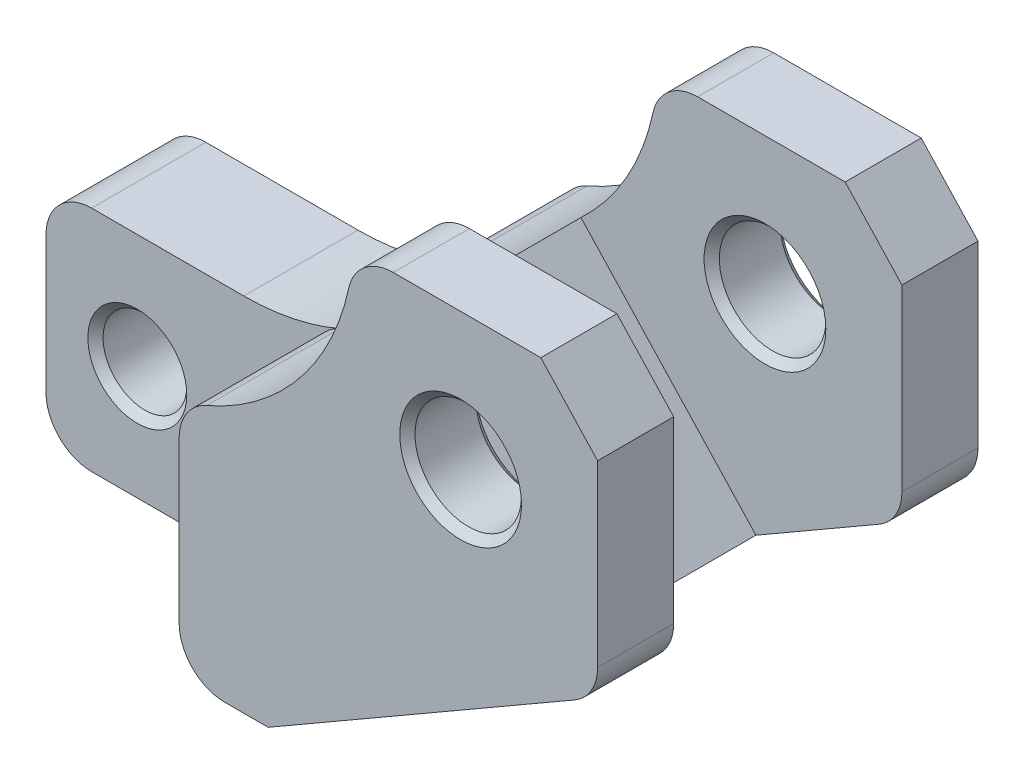
SolidWorks part; units mm, degrees
ref_plane "Front Plane" through (0, 0, 0) normal (0, 0, 1) x (1, 0, 0)
ref_plane "Top Plane" through (0, 0, 0) normal (0, 1, 0) x (1, 0, 0)
ref_plane "Right Plane" through (0, 0, 0) normal (1, 0, 0) x (0, 0, -1)
sketch "Sketch1" plane through (0, 0, 0) normal (0, 0, 1) x (1, 0, 0)
  line L0 (0, 24000) -> (0, 6000)
  line L1 (6000, 0) -> (46698.7298, 0)
  line L2 (46698.7298, 0) -> (87000, 23267.9492)
  line L3 (90000, 28464.1016) -> (90000, 60000)
  line L4 (90000, 60000) -> (63148.3512, 60000)
  line L5 (6000, 30000) -> (26000, 30000)
  arc A0 (26000, 30000) -> (57282.8221, 55263.1579) centre (26000, 62000) ccw
  arc A1 (87000, 23267.9492) -> (90000, 28464.1016) centre (84000, 28464.1016) ccw
  arc A2 (63148.3512, 60000) -> (57282.8221, 55263.1579) centre (63148.3512, 54000) ccw
  arc A3 (0, 6000) -> (6000, 0) centre (6000, 6000) ccw
  arc A4 (0, 24000) -> (6000, 30000) centre (6000, 24000) cw
  point P9 (28220.4792, 51998.0458)
  point P10 (90000, 41829.3302)
  point P11 (90000, 0)
  point P12 (90000, 32721.6643)
  point P15 (90000, 25000)
  point P20 (0, 0)
  point P23 (0, 0)
  dimension "D1" = 32000
  dimension "D8" = 6000
  dimension "D2" = 90000
  dimension "D3" = 30
  dimension "D4" = 25000
  dimension "D5" = 60000
  dimension "D6" = 30000
  dimension "D7" = 26000
extrude "Boss-Extrude1" add sketch "Sketch1" along normal mid plane 50000
chamfer "Chamfer1" distance 8000 angle 43 1 edges at (90000, 60000, 0)
sketch "Sketch4" plane through (0, 0, 0) normal (0, 0, 1) x (1, 0, 0)
  line L0 (70814.2066, 13923.077) -> (47814.1845, 38587.5812)
  line L10 (90000, 28464.1016) -> (90000, 52000)
  line L11 (90000, 52000) -> (82539.8793, 60000)
  line L12 (82539.8793, 60000) -> (63148.3512, 60000)
  line L13 (26000, 30000) -> (6000, 30000)
  line L14 (0, 24000) -> (0, 6000)
  line L15 (6000, 0) -> (46698.7298, 0)
  line L16 (46698.7298, 0) -> (87000, 23267.9492)
  line L17 (90000, 28464.1016) -> (90000, 52000)
  line L18 (90000, 52000) -> (82539.8793, 60000)
  line L19 (82539.8793, 60000) -> (63148.3512, 60000)
  line L23 (70814.2066, 13923.077) -> (87000, 23267.9492)
  arc A6 (63148.3512, 60000) -> (57282.8221, 55263.1579) centre (63148.3512, 54000) ccw
  arc A7 (26000, 30000) -> (57282.8221, 55263.1579) centre (26000, 62000) ccw
  arc A8 (6000, 30000) -> (0, 24000) centre (6000, 24000) ccw
  arc A9 (0, 6000) -> (6000, 0) centre (6000, 6000) ccw
  arc A10 (87000, 23267.9492) -> (90000, 28464.1016) centre (84000, 28464.1016) ccw
  arc A11 (63148.3512, 60000) -> (57282.8221, 55263.1579) centre (63148.3512, 54000) ccw
  arc A12 (47814.1845, 38587.5812) -> (57282.8221, 55263.1579) centre (26000, 62000) ccw
  arc A15 (87000, 23267.9492) -> (90000, 28464.1016) centre (84000, 28464.1016) ccw
  dimension "D1" = 40000
  dimension "D2" = 0
extrude "Cut-Extrude1" cut sketch "Sketch4" against normal mid plane 30000
sketch "Sketch5" plane through (0, 0, 25000) normal (0, 0, 1) x (1, 0, 0)
  line L0 (35000, 0) -> (35000, 31291.6949)
  line L1 (6000, 0) -> (46698.7298, 0) construction
  line L9 (90000, 28464.1016) -> (90000, 52000)
  line L10 (90000, 52000) -> (82539.8793, 60000)
  line L11 (82539.8793, 60000) -> (63148.3512, 60000)
  line L12 (26000, 30000) -> (6000, 30000)
  line L13 (0, 24000) -> (0, 6000)
  line L14 (6000, 0) -> (46698.7298, 0)
  line L15 (46698.7298, 0) -> (87000, 23267.9492)
  line L19 (26000, 30000) -> (6000, 30000)
  line L20 (0, 24000) -> (0, 6000)
  line L21 (6000, 0) -> (35000, 0)
  arc A0 (26000, 30000) -> (57282.8221, 55263.1579) centre (26000, 62000) ccw construction
  arc A6 (63148.3512, 60000) -> (57282.8221, 55263.1579) centre (63148.3512, 54000) ccw
  arc A7 (26000, 30000) -> (57282.8221, 55263.1579) centre (26000, 62000) ccw
  arc A8 (6000, 30000) -> (0, 24000) centre (6000, 24000) ccw
  arc A9 (0, 6000) -> (6000, 0) centre (6000, 6000) ccw
  arc A10 (87000, 23267.9492) -> (90000, 28464.1016) centre (84000, 28464.1016) ccw
  arc A12 (26000, 30000) -> (35000, 31291.6949) centre (26000, 62000) ccw
  arc A13 (6000, 30000) -> (0, 24000) centre (6000, 24000) ccw
  arc A14 (0, 6000) -> (6000, 0) centre (6000, 6000) ccw
  dimension "D2" = 35000
  dimension "D1" = 0
extrude "Cut-Extrude2" cut sketch "Sketch5" against normal blind 17500
mirror "Mirror2" about plane through (0, 0, 0) normal (0, 0, 1) of "Cut-Extrude2"
fillet "Fillet1" radius 6000 2 edges at (35000, 0, 16250) (35000, 31291.6949, 16250)
sketch "Sketch6" plane through (0, 0, 7500) normal (0, 0, 1) x (1, 0, 0)
  line L0 (6000, 0) -> (41000, 0) construction
  line L1 (0, 24000) -> (0, 6000) construction
  circle A0 centre (12000, 15000) radius 5500
  dimension "D1" = 11000
  dimension "D2" = 15000
  dimension "D3" = 12000
extrude "Cut-Extrude3" cut sketch "Sketch6" against normal through all both and the other way through all
sketch "Sketch7" plane through (0, 0, 25000) normal (0, 0, 1) x (1, 0, 0)
  line L0 (82539.8793, 60000) -> (63148.3512, 60000) construction
  line L1 (90000, 28464.1016) -> (90000, 52000) construction
  circle A0 centre (72000, 42000) radius 7000
  point P2 (0, 0)
  point P5 (0, 0)
  dimension "D1" = 14000
  dimension "D2" = 18000
  dimension "D3" = 18000
extrude "Cut-Extrude4" cut sketch "Sketch7" against normal through all both and the other way through all
chamfer "Chamfer2" distance 1000 angle 45 3 edges at (79000, 42000, 25000) (79000, 42000, 15000) (17500, 15000, 7500)
chamfer "Chamfer3" distance 1000 angle 45 3 edges at (6500, 15000, -7500) (79000, 42000, -25000) (79000, 42000, -15000)
fillet "Fillet2" radius 6000 2 edges at (35000, 0, -16250) (35000, 31291.6949, -16250)
